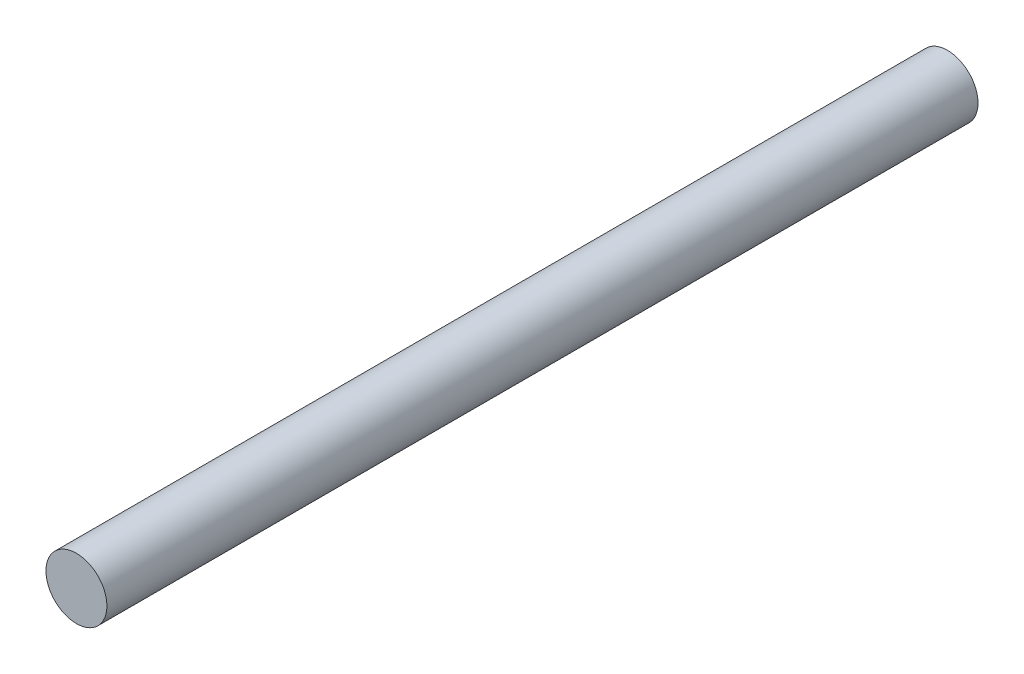
SolidWorks part; units mm, degrees
ref_plane "Alzado" through (0, 0, 0) normal (0, 0, 1) x (1, 0, 0)
ref_plane "Planta" through (0, 0, 0) normal (0, 1, 0) x (1, 0, 0)
ref_plane "Vista lateral" through (0, 0, 0) normal (1, 0, 0) x (0, 0, -1)
sketch "Croquis1" plane through (0, 0, 0) normal (0, 0, 1) x (1, 0, 0)
  circle A0 centre (0, 0) radius 0.63
  dimension "D1" = 1.26
extrude "Saliente-Extruir1" add sketch "Croquis1" along normal blind 18 contours A0
equation "\"t\"= 4"
equation "\"A_ALETA\"= ( ( ( tan ( \"ANG_ALETA\" ) ) * \"L_ALETA\" ) + \"A_BASE\" - ( \"GAP_ALETAS\" / 2 ) )"
equation "\"A_CAJA\"= ( 2 * \"A_BASE\" ) + \"GAP_ALETAS\""
equation "\"L_ALETA\"=90.000000"
equation "\"TAU_ALETA\"= ( \"L_ALETA\" / ( log ( ( \"A_ALETA\" ) + 1 ) ) )"
equation "\"E_ALETA\"=5.000000"
equation "\"R_SONDA\"= 2.05"
equation "\"D_SONDA\"=20.000000"
equation "\"L_CAJA\"=25.000000"
equation "\"D1@Croquis1\" = ( \"R_C_SONDA\" * 2 )"
equation "\"D1@Saliente-Extruir1\" = \"L_CI\""
equation "\"A_BASE\"= ( \"L_DIE\" - \"E_CAJA\" )"
equation "\"E_CAJA\"= 2.5"
equation "\"W_CAJA\"= \"A_CAJA\" * \"CONST_CAJA\""
equation "\"W_CONC\"= ( \"W_CAJA\" / \"CONST_CONC\" ) "
equation "\"A_CONC\"= ( \"A_CAJA\" / \"CONST_CONC\" )"
equation "\"L_CONC\"= \"D_SONDA\" - \"OFFSET_CONC\""
equation "\"W_ALETA\"=70.000000"
equation "\"GAP_ALETAS\"=1.500000"
equation "\"D1@Croquis2\" = ( \"E_CI_SONDA\" )"
equation "\"D1@Saliente-Extruir2\" = \"GAP_ALETAS\" / 2"
equation "\"D1@Croquis3\" = ( \"R_SONDA\" - \"E_CE_SONDA\" ) * 2"
equation "\"D2@Croquis3\" = \"E_CI_SONDA\""
equation "\"L_DIE_SONDA\"= ( \"GAP_ALETAS\" / 4 )"
equation "\"D1@Croquis4\" = ( \"E_CI_SONDA\" * 2 )"
equation "\"D2@Croquis4\" = ( \"R_SONDA\" - \"E_CE_SONDA\" ) * 2"
equation "\"D1@Saliente-Extruir4\" = \"A_BASE\" + \"E_CAJA\" + \"L_DIE_SONDA\""
equation "\"D1@Croquis5\" = ( \"R_SONDA\" - \"E_CE_SONDA\" ) * 2"
equation "\"D2@Croquis5\" = 2 * \"R_SONDA\""
equation "\"D1@Saliente-Extruir5\" = \"E_CAJA\" + \"A_BASE\""
equation "\"CONST_CONC\"=2.000000"
equation "\"K\"= 1.5"
equation "\"L_DIE\"= 15"
equation "\"L_CI\"= 18"
equation "\"CONST_CAJA\"=2.000000"
equation "\"ANG_ALETA\"=15.000000"
equation "\"R_C_SONDA\"= 0.63"
equation "\"TOLERANCIA\"= 0.1"
equation "\"OFFSET_CONC\"= ( 2 * \"R_TORNILLO\" )"
equation "\"R_TORNILLO\"=2.600000"
